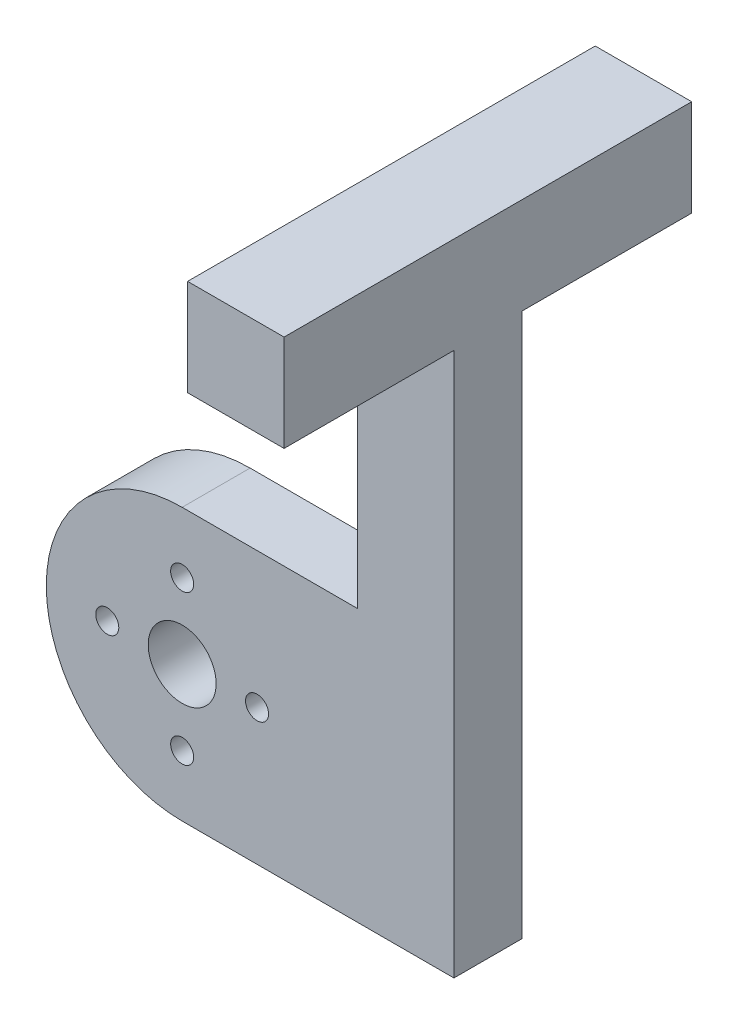
SolidWorks part; units mm, degrees
ref_plane "Front Plane" through (0, 0, 0) normal (0, 0, 1) x (1, 0, 0)
ref_plane "Top Plane" through (0, 0, 0) normal (0, 1, 0) x (1, 0, 0)
ref_plane "Right Plane" through (0, 0, 0) normal (1, 0, 0) x (0, 0, -1)
sketch "Sketch2" plane through (0, 0, 0) normal (0, 0, 1) x (1, 0, 0)
  line L0 (16.383, 47.117) -> (25.4, 47.117)
  line L1 (16.383, 47.117) -> (16.383, 12.7)
  line L2 (16.383, 12.7) -> (0, 12.7)
  line L3 (25.4, 47.117) -> (25.4, -12.7)
  line L4 (25.4, -12.7) -> (0, -12.7)
  circle A0 centre (0, 0) radius 12.7
  circle A1 centre (7, 0) radius 1.077
  circle A2 centre (0, -7) radius 1.077
  circle A3 centre (-7, 0) radius 1.077
  circle A4 centre (0, 7) radius 1.077
  point P14 (0, 0)
  dimension "D1" = 25.4
  dimension "D3" = 2.154
  dimension "D2" = 7
  dimension "D5" = 47.117
  dimension "D6" = 16.383
  dimension "D7" = 25.4
  dimension "D8" = 9.017
  dimension "D4" = 4
extrude "Boss-Extrude1" add sketch "Sketch2" along normal mid plane 6.35 contours A0 L4 L3 L0 L1 L2 | A0 A4 A3 A2 A1
sketch "Sketch3" plane through (0, 0, 0) normal (0, 0, -1) x (-1, 0, 0)
  line L0 (-16.383, 47.117) -> (-16.383, 12.7) construction
  line L1 (-25.4, 47.117) -> (-16.383, 47.117)
  line L2 (-25.4, 47.117) -> (-25.4, 38.1)
  line L3 (-25.4, 38.1) -> (-16.383, 38.1)
  line L4 (-16.383, 47.117) -> (-16.383, 38.1)
extrude "Boss-Extrude2" add sketch "Sketch3" along normal mid plane 38.1
sketch "Sketch4" plane through (0, 0, 3.175) normal (0, 0, 1) x (1, 0, 0)
  circle A0 centre (0, 0) radius 3.175
  dimension "D1" = 6.35
extrude "Cut-Extrude1" cut sketch "Sketch4" against normal through all
equation "\"D2@Sketch2\"=7mm"
equation "\"tightTol\"= 0.005in"
equation "\"normTol\"= 0.01in"
equation "\"looseTol\"= 0.02in"
equation "\"D3@Sketch2\"=1.9mm+\"normTol\""
equation "\"D6@Sketch2\"=0.625+\"looseTol\""
equation "\"D5@Sketch2\"=1.875-\"looseTol\""
